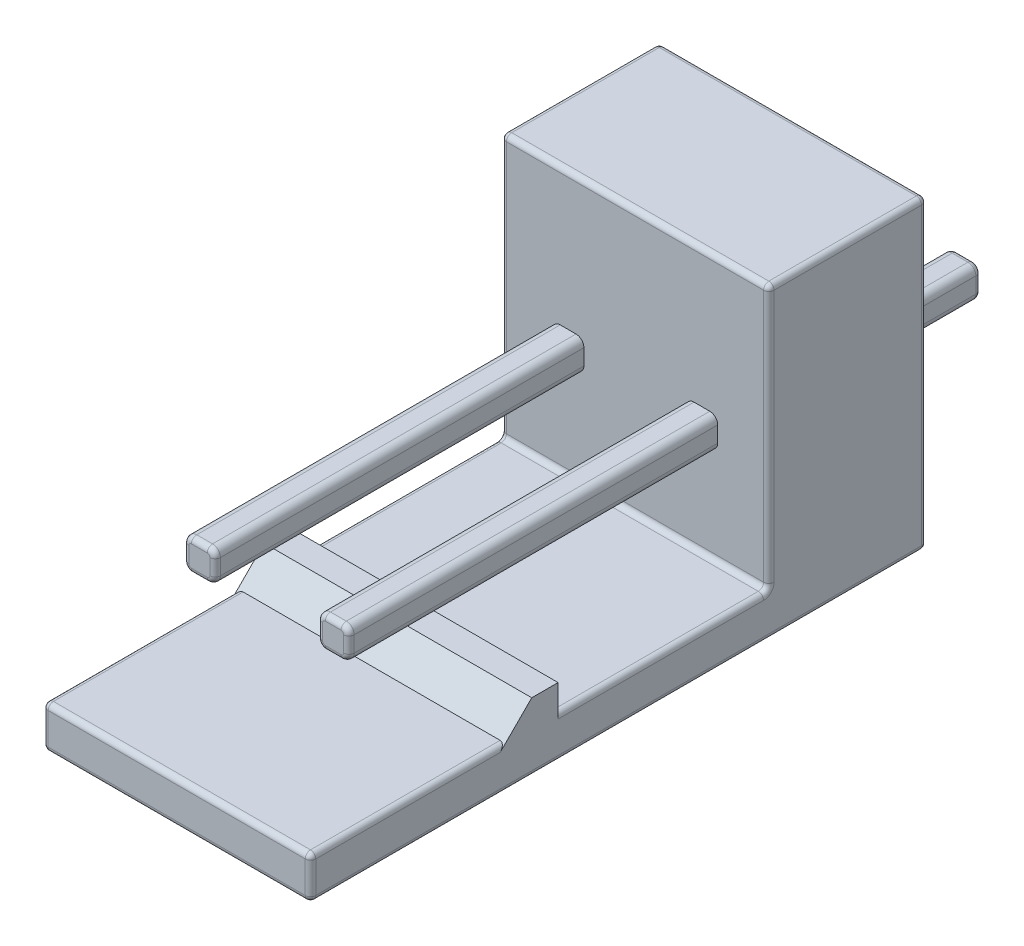
SolidWorks part; units mm, degrees
ref_plane "前视基准面" through (0, 0, 0) normal (0, 0, 1) x (1, 0, 0)
ref_plane "上视基准面" through (0, 0, 0) normal (0, 1, 0) x (1, 0, 0)
ref_plane "右视基准面" through (0, 0, 0) normal (1, 0, 0) x (0, 0, -1)
sketch "草图1" plane through (0, 0, 0) normal (0, 0, 1) x (1, 0, 0)
  line L0 (-1000, 0) -> (49000, 0) construction
  line L1 (0, -1000) -> (0, 49000) construction
  line L2 (-2.54, 2.9) -> (-2.54, -2.9)
  line L3 (-2.54, -2.9) -> (2.54, -2.9)
  line L4 (-2.54, 2.9) -> (2.54, 2.9)
  line L5 (2.54, 2.9) -> (2.54, -2.9)
  point P10 (-2.54, 0)
  point P11 (0, -2.9)
  point P12 (0, 2.9)
  dimension "D1" = 5.08
  dimension "D2" = 5.8
extrude "凸台-拉伸1" add sketch "草图1" along normal blind 11.7
sketch "草图2" plane through (2.54, 0, 0) normal (1, 0, 0) x (0, 0, -1)
  line L0 (-11.7, -2.1) -> (-8, -2.1)
  line L1 (-11.7, -2.9) -> (-11.7, 2.9) construction
  line L2 (-3, -2.1) -> (-3, 2.9)
  line L3 (-11.7, 2.9) -> (0, 2.9) construction
  line L4 (-3, 2.9) -> (-11.7, 2.9)
  line L5 (-11.7, 2.9) -> (-11.7, -2.1)
  line L6 (0, -2.9) -> (0, 2.9) construction
  line L7 (-11.7, -2.9) -> (0, -2.9) construction
  line L8 (-7.5, -1.6) -> (-7, -1.6)
  line L9 (-7, -2.1) -> (-7, -1.6)
  line L10 (-7, -2.1) -> (-3, -2.1)
  line L12 (-8, -2.1) -> (-7.5, -1.6)
  dimension "D1" = 3
  dimension "D2" = 0.8
  dimension "D3" = 0.5
  dimension "D4" = 4
extrude "切除-拉伸1" cut sketch "草图2" against normal through all
sketch "草图3" plane through (0, 0, 0) normal (0, 0, -1) x (-1, 0, 0)
  line L0 (-2.54, 0) -> (2.54, 0) construction
  line L1 (-2.54, -2.9) -> (-2.54, 2.9) construction
  line L2 (2.54, 2.9) -> (2.54, -2.9) construction
  line L3 (0, -2.9) -> (0, 2.9) construction
  line L4 (2.54, -2.9) -> (-2.54, -2.9) construction
  line L5 (-2.54, 2.9) -> (2.54, 2.9) construction
  line L6 (-1.27, -1.0013) -> (-1.27, 0.9265) construction
  line L7 (-1.57, -0.15) -> (-1.57, 0.15)
  line L8 (-1.42, -0.3) -> (-1.12, -0.3)
  line L9 (-0.97, -0.15) -> (-0.97, 0.15)
  line L10 (-1.42, 0.3) -> (-1.12, 0.3)
  arc A0 (-1.12, 0.3) -> (-0.97, 0.15) centre (-1.12, 0.15) cw
  arc A1 (-0.97, -0.15) -> (-1.12, -0.3) centre (-1.12, -0.15) cw
  arc A2 (-1.42, 0.3) -> (-1.57, 0.15) centre (-1.42, 0.15) ccw
  arc A3 (-1.57, -0.15) -> (-1.42, -0.3) centre (-1.42, -0.15) ccw
  point P18 (-1.27, -0.3)
  point P20 (-0.97, 0)
  point P21 (-1.57, 0)
  point P23 (-0.97, 0.3)
  point P26 (-0.97, -0.3)
  point P29 (-1.57, 0.3)
  point P32 (-1.57, -0.3)
  dimension "D4" = 0.15
  dimension "D1" = 1.27
  dimension "D2" = 0.6
  dimension "D3" = 0.6
extrude "凸台-拉伸2" add sketch "草图3" along normal blind 2 and the other way blind 10
fillet "圆角1" radius 0.1 16 edges at (1.5261, 0.2561, 10) (1.27, 0.3, 10) (1.0139, 0.2561, 10) (0.97, 0, 10) (1.0139, -0.2561, 10) (1.27, -0.3, 10) (1.5261, -0.2561, 10) (1.0139, 0.2561, -2) (0.97, 0, -2) (1.0139, -0.2561, -2) (1.27, -0.3, -2) (1.5261, -0.2561, -2) (1.57, 0, -2) (1.5261, 0.2561, -2) (1.57, 0, 10) (1.27, 0.3, -2)
fillet "圆角2" radius 0.1 20 edges at (-2.54, -2.1, 5) (2.54, -2.1, 5) (2.54, -2.1, 9.85) (2.54, -2.5, 11.7) (-2.54, -2.1, 9.85) (-2.54, -2.5, 11.7) (0, -2.1, 11.7) (2.54, -2.9, 5.85) (0, -2.9, 11.7) (-2.54, -2.9, 5.85) (0, -2.1, 3) (-2.54, 0.4, 3) (0, -2.9, 0) (-2.54, 0, 0) (2.54, 2.9, 1.5) (-2.54, 2.9, 1.5) (0, 2.9, 0) (2.54, 0, 0) (2.54, 0.4, 3) (0, 2.9, 3)
mirror "镜向2" about plane through (0, 0, 0) normal (1, 0, 0) of "圆角1", "凸台-拉伸2"
